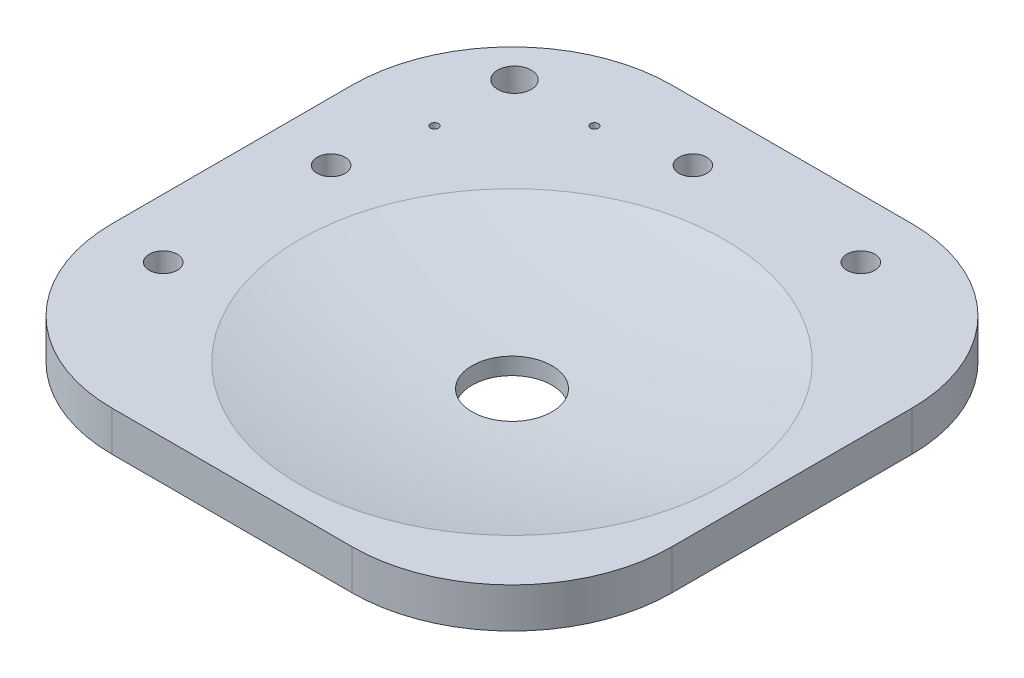
SolidWorks part; units mm, degrees
ref_plane "Front Plane" through (0, 0, 0) normal (0, 0, 1) x (1, 0, 0)
ref_plane "Top Plane" through (0, 0, 0) normal (0, 1, 0) x (1, 0, 0)
ref_plane "Right Plane" through (0, 0, 0) normal (1, 0, 0) x (0, 0, -1)
sketch "Sketch1" plane through (0, 0, 0) normal (0, 1, 0) x (1, 0, 0)
  line L1 (-30, -30) -> (30, -30)
  line L2 (-30, -30) -> (-30, 30)
  line L3 (-30, 30) -> (30, 30)
  line L4 (30, -30) -> (30, 30)
  point P0 (0, 0)
  dimension "D1" = 60
  dimension "D2" = 60
extrude "Boss-Extrude1" add sketch "Sketch1" along normal blind 5
sketch "Sketch2" plane through (0, 5, 0) normal (0, 1, 0) x (1, 0, 0)
  circle A0 centre (0, 0) radius 5
  dimension "D1" = 10
extrude "Cut-Extrude1" cut sketch "Sketch2" against normal through all
sketch "Sketch3" plane through (0, 0, 0) normal (0, 0, 1) x (1, 0, 0)
  line L0 (0, 2.0073) -> (0, 240.6873)
  arc A0 (0, 2.0073) -> (0, 240.6873) centre (0, 121.3473) ccw
revolve "Cut-Revolve1" cut sketch "Sketch3" angle 360 about L0
sketch "Sketch5" plane through (0, 0, 0) normal (0, 1, 0) x (1, 0, 0)
  line L0 (-30, -30) -> (-40, -30)
  line L1 (-30, 30) -> (-30, -30) construction
  line L2 (-40, -30) -> (-40, 40)
  line L3 (-40, 40) -> (30, 40)
  line L4 (30, 40) -> (30, 30)
  line L5 (30, -30) -> (30, 30) construction
  line L6 (30, 30) -> (-30, 30)
  line L7 (30, 30) -> (-30, 30) construction
  line L8 (-30, 30) -> (-30, -30)
  dimension "D1" = 10
  dimension "D2" = 10
extrude "Boss-Extrude2" add sketch "Sketch5" along normal blind 5
sketch "Sketch4" plane through (0, 5, 0) normal (0, 1, 0) x (1, 0, 0)
  line L0 (-32.6274, 10) -> (-10, 10) construction
  line L3 (-10, 10) -> (-10, 32.6274) construction
  line L4 (-32.6274, 10) -> (-10, 32.6274) construction
  line L7 (-32.6274, -11) -> (-32.6274, 10) construction
  line L8 (-10, 32.6274) -> (11, 32.6274) construction
  line L9 (0, 0) -> (-21.3137, 21.3137) construction
  circle A0 centre (-32.6274, 10) radius 1.75
  circle A1 centre (-10, 32.6274) radius 1.75
  circle A2 centre (11, 32.6274) radius 1.75
  circle A3 centre (-32.6274, -11) radius 1.75
  dimension "D3" = 3.5
  dimension "D2" = 32
  dimension "D4" = 21
  dimension "D5" = 21
  dimension "D6" = 10
  dimension "D7" = 10
extrude "Cut-Extrude2" cut sketch "Sketch4" against normal through all
fillet "Fillet1" radius 20 4 edges at (30, 2.5, 30) (30, 2.5, -40) (-40, 2.5, -40) (-40, 2.5, 30)
sketch "Sketch8" plane through (0, 5, 0) normal (0, 1, 0) x (1, 0, 0)
  circle A0 centre (-30.4282, 30.7374) radius 2.1
  circle A1 centre (-20.4282, 30.7374) radius 0.5
  circle A2 centre (-30.4282, 20.7374) radius 0.5
  point P6 (-31.0729, 26.9685)
  point P7 (-32.1702, 33.1265)
  point P8 (0, 0)
  point P9 (0, 0)
  point P10 (-30.4282, 30.7374)
  dimension "D3" = 1
  dimension "D4" = 4.2
  dimension "D1" = 10
  dimension "D2" = 10
extrude "Cut-Extrude3" cut sketch "Sketch8" against normal blind 10
